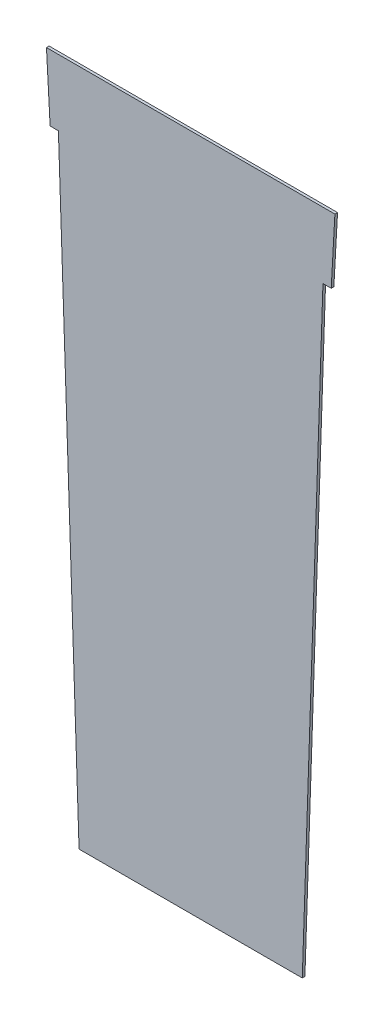
SolidWorks part; units mm, degrees
ref_plane "Front Plane" through (0, 0, 0) normal (0, 0, 1) x (1, 0, 0)
ref_plane "Top Plane" through (0, 0, 0) normal (0, 1, 0) x (1, 0, 0)
ref_plane "Right Plane" through (0, 0, 0) normal (1, 0, 0) x (0, 0, -1)
sketch "Sketch1" plane through (0, 0, 0) normal (0, 0, 1) x (1, 0, 0)
  line L0 (0, 0) -> (221.5444, 0)
  line L1 (0, 0) -> (0, -520.7) construction
  line L2 (25.0472, -520.7) -> (196.4972, -520.7)
  line L3 (0, -50.8) -> (300.2753, -50.8) construction
  line L4 (2.8222, -50.8) -> (218.7222, -50.8)
  line L5 (0, 0) -> (2.8222, -50.8)
  line L6 (221.5444, 0) -> (218.7222, -50.8)
  line L7 (196.4972, -520.7) -> (212.3722, -50.8)
  line L8 (9.1722, -50.8) -> (25.0472, -520.7)
  point P6 (110.7722, 0)
  point P7 (110.7722, -520.7)
  point P12 (110.7722, -50.8)
  dimension "D1" = 50.8
  dimension "D2" = 93.18
  dimension "D3" = 171.45
  dimension "D4" = 469.9
  dimension "D5" = 215.9
  dimension "D6" = 6.35
  dimension "D7" = 6.35
extrude "Boss-Extrude1" add sketch "Sketch1" along normal blind 2.032 contours L6 L0 L5 L4 | L4 L8 L2 L7
